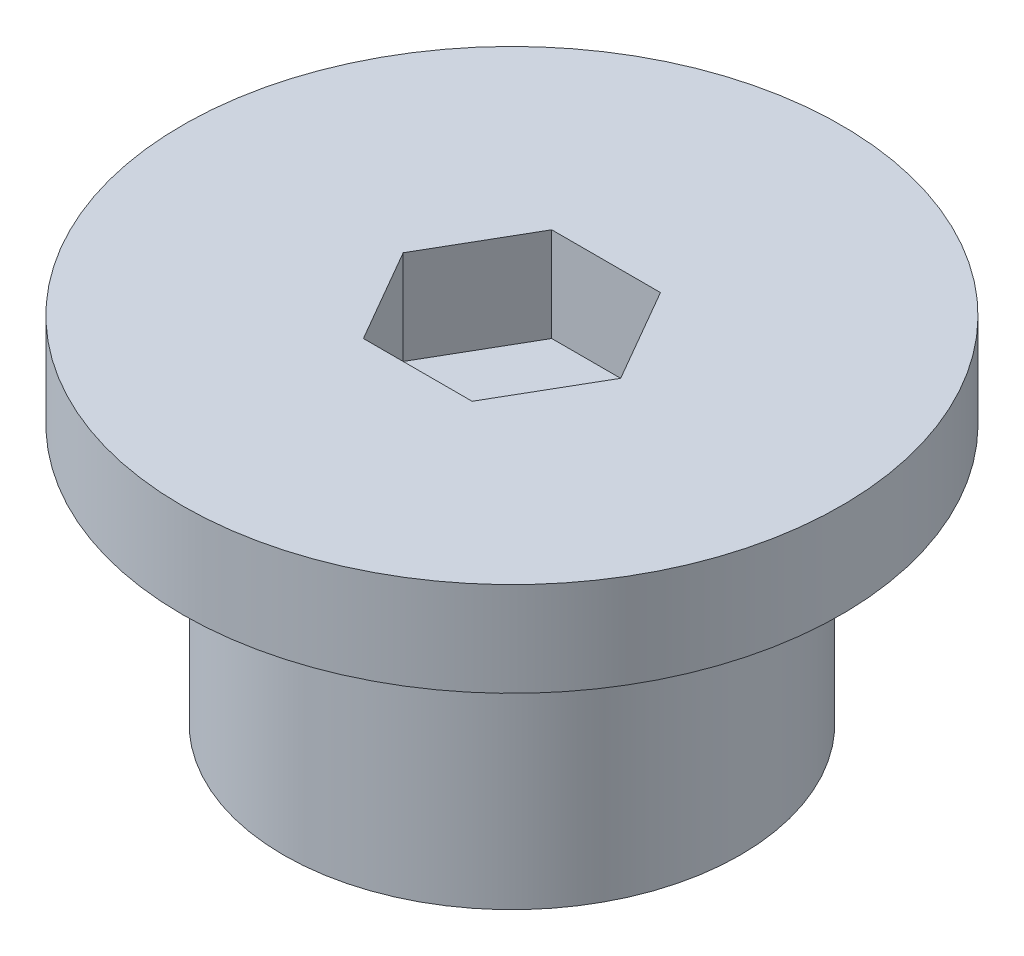
SolidWorks part; units mm, degrees
ref_plane "Спереди" through (0, 0, 0) normal (0, 0, 1) x (1, 0, 0)
ref_plane "Сверху" through (0, 0, 0) normal (0, 1, 0) x (1, 0, 0)
ref_plane "Справа" through (0, 0, 0) normal (1, 0, 0) x (0, 0, -1)
sketch "Эскиз1" plane through (0, 0, 0) normal (0, 0, 1) x (1, 0, 0)
  line L0 (0, 21.4393) -> (0, -16.0678) construction
  line L1 (0, 7.5) -> (7, 7.5)
  line L2 (0, 0) -> (4.85, 0)
  line L3 (4.85, 0) -> (4.85, 5.5)
  line L4 (4.85, 5.5) -> (7, 5.5)
  line L5 (7, 5.5) -> (7, 7.5)
  line L6 (0, 7.5) -> (0, 0)
  dimension "D1" = 14
  dimension "D2" = 7.5
  dimension "D3" = 5.5
  dimension "D4" = 9.7
revolve "Повернуть1" add sketch "Эскиз1" angle 360 about L0
sketch "Эскиз2" plane through (0, 7.5, 0) normal (0, 1, 0) x (1, 0, 0)
  line L1 (2.3094, 0) -> (1.1547, 2)
  line L2 (1.1547, 2) -> (-1.1547, 2)
  line L3 (-1.1547, 2) -> (-2.3094, 0)
  line L4 (-2.3094, 0) -> (-1.1547, -2)
  line L5 (-1.1547, -2) -> (1.1547, -2)
  line L6 (1.1547, -2) -> (2.3094, 0)
  circle A0 centre (0, 0) radius 2 construction
  dimension "D1" = 4
extrude "Вырез-Вытянуть1" cut sketch "Эскиз2" against normal blind 2
